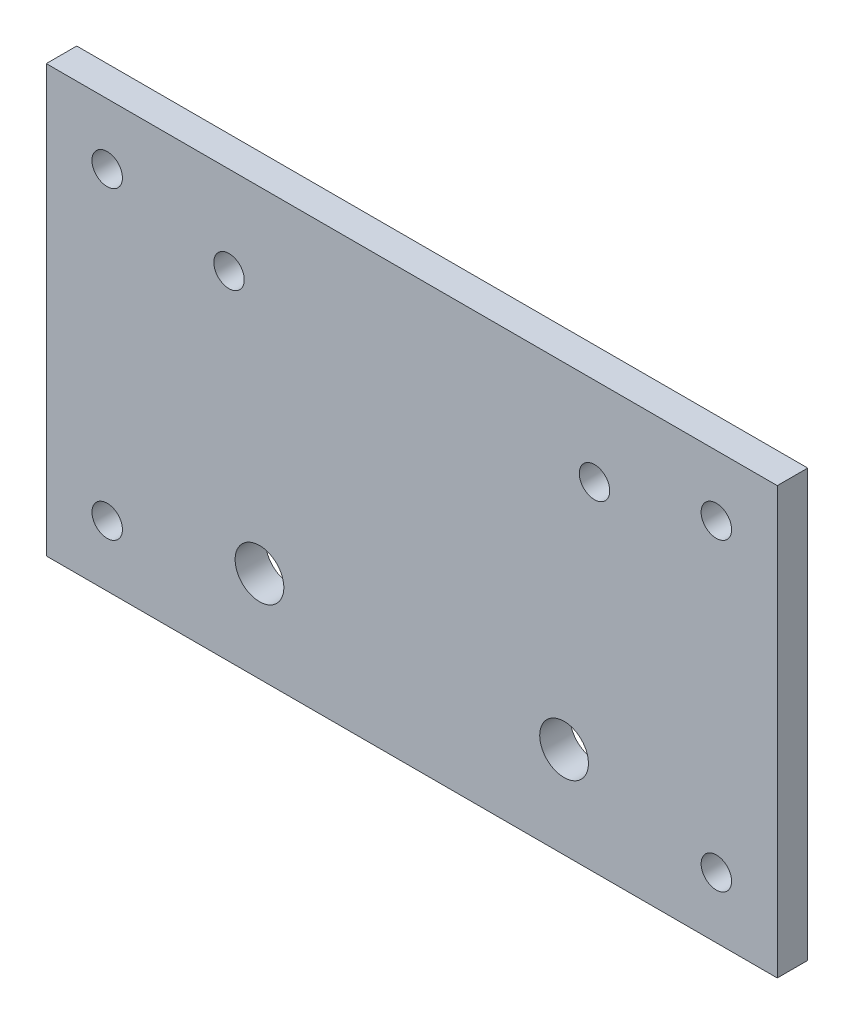
SolidWorks part; units mm, degrees
ref_plane "Front Plane" through (0, 0, 0) normal (0, 0, 1) x (1, 0, 0)
ref_plane "Top Plane" through (0, 0, 0) normal (0, 1, 0) x (1, 0, 0)
ref_plane "Right Plane" through (0, 0, 0) normal (1, 0, 0) x (0, 0, -1)
sketch "Sketch1" plane through (0, 0, 0) normal (0, 0, 1) x (1, 0, 0)
  line L0 (60, 0) -> (60, -70) construction
  line L1 (0, 0) -> (39, 0)
  line L2 (0, 0) -> (0, -70)
  line L3 (0, -70) -> (120, -70)
  line L4 (120, 0) -> (120, -70)
  line L5 (0, -35) -> (120, -35) construction
  line L12 (81, 0) -> (120, 0)
  line L13 (39, 0) -> (81, 0)
  circle A5 centre (35, -55) radius 4
  circle A6 centre (85, -55) radius 4
  circle A7 centre (10, -10) radius 2.5
  circle A8 centre (110, -10) radius 2.5
  circle A9 centre (110, -60) radius 2.5
  circle A10 centre (10, -60) radius 2.5
  circle A11 centre (30, -14.5) radius 2.5
  circle A12 centre (90, -14.5) radius 2.5
  dimension "D7" = 8
  dimension "D10" = 5
  dimension "D13" = 5
  dimension "D1" = 70
  dimension "D2" = 120
  dimension "D8" = 25
  dimension "D9" = 20
  dimension "D11" = 10
  dimension "D12" = 10
  dimension "D14" = 30
  dimension "D15" = 20.5
extrude "Boss-Extrude1" add sketch "Sketch1" along normal blind 5
